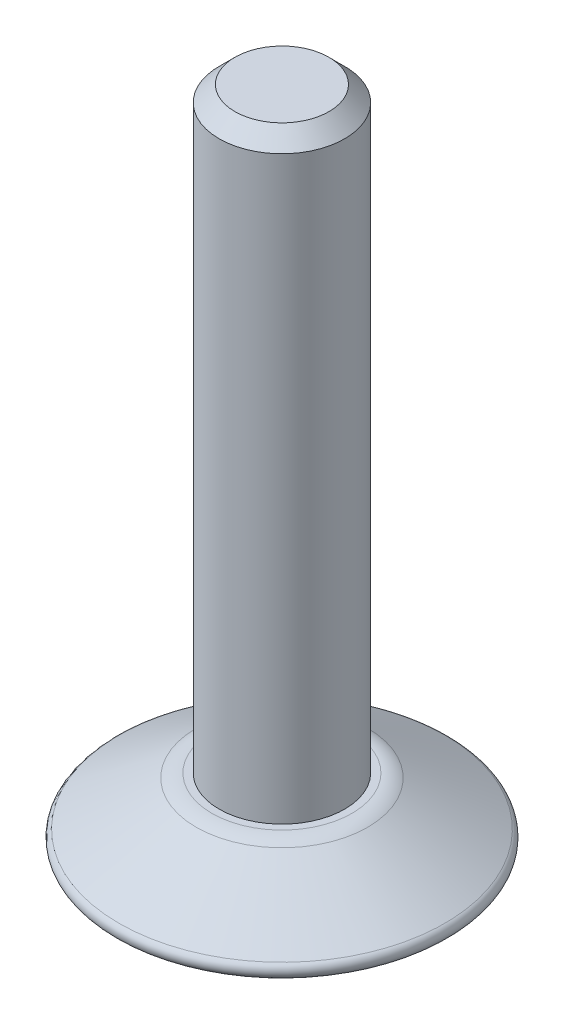
SolidWorks part; units mm, degrees
ref_plane "Front Plane" through (0, 0, 0) normal (0, 0, 1) x (1, 0, 0)
ref_plane "Top Plane" through (0, 0, 0) normal (0, 1, 0) x (1, 0, 0)
ref_plane "Right Plane" through (0, 0, 0) normal (1, 0, 0) x (0, 0, -1)
sketch "Sketch1" plane through (0, 0, 0) normal (0, 1, 0) x (1, 0, 0)
  circle A0 centre (0, 0) radius 6
  dimension "D1" = 12
extrude "Boss-Extrude1" add sketch "Sketch1" along normal blind 10
chamfer "Chamfer1" distance 3.5 angle 30 1 edges at (0, 10, 6)
sketch "Sketch2" plane through (0, 0, 0) normal (0, 0, 1) x (1, 0, 0)
  line L1 (-6, 7.9793) -> (6, 7.9793)
  line L2 (-6, 7.9793) -> (-6, 0)
  line L3 (-6, 0) -> (6, 0)
  line L4 (6, 7.9793) -> (6, 0)
extrude "Cut-Extrude1" cut sketch "Sketch2" against normal through all both and the other way through all
sketch "Sketch3" plane through (0, 10, 0) normal (0, 1, 0) x (1, 0, 0)
  circle A0 centre (0, 0) radius 2
  dimension "D1" = 4
extrude "Boss-Extrude2" add sketch "Sketch3" along normal blind 19
chamfer "Chamfer2" distance 0.5 angle 45 1 edges at (0, 29, 2)
fillet "Fillet1" radius 0.25 1 edges at (0, 7.9793, 6)
fillet "Fillet2" radius 1 1 edges at (0, 10, 2.5)
